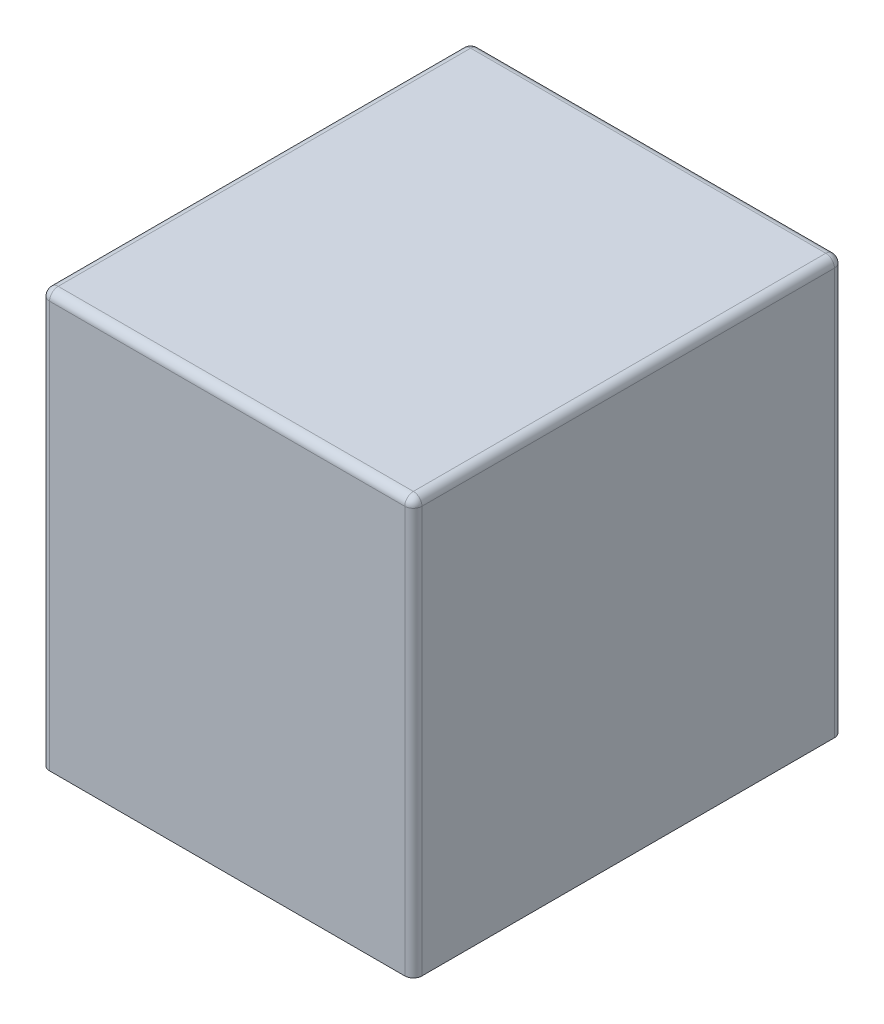
SolidWorks part; units mm, degrees
ref_plane "前视基准面" through (0, 0, 0) normal (0, 0, 1) x (1, 0, 0)
ref_plane "上视基准面" through (0, 0, 0) normal (0, 1, 0) x (1, 0, 0)
ref_plane "右视基准面" through (0, 0, 0) normal (1, 0, 0) x (0, 0, -1)
sketch "Sketch1" plane through (0, 0, 0) normal (0, 1, 0) x (1, 0, 0)
  line L0 (-65, 75) -> (65, 75)
  line L1 (-60, 70) -> (60, 70)
  line L2 (-60, 70) -> (-60, -70)
  line L3 (-60, -70) -> (60, -70)
  line L4 (60, 70) -> (60, -70)
  line L5 (-60, 70) -> (60, -70) construction
  line L6 (-60, -70) -> (60, 70) construction
  line L7 (65, 75) -> (65, -75)
  line L8 (-65, -75) -> (65, -75)
  line L9 (-65, 75) -> (-65, -75)
  point P0 (0, 0)
  dimension "D1" = 120
  dimension "D2" = 140
  dimension "D3" = 5
extrude "Boss-Extrude1" add sketch "Sketch1" along normal blind 140
sketch "Sketch2" plane through (0, 140, 0) normal (0, 1, 0) x (1, 0, 0)
  line L4 (-65, 75) -> (-65, -75)
  line L5 (-65, -75) -> (65, -75)
  line L6 (65, -75) -> (65, 75)
  line L7 (65, 75) -> (-65, 75)
  line L8 (-65, 75) -> (-65, -75)
  line L9 (-65, -75) -> (65, -75)
  line L10 (65, -75) -> (65, 75)
  line L11 (65, 75) -> (-65, 75)
  dimension "D1" = 0
extrude "Boss-Extrude2" add sketch "Sketch2" along normal blind 5
sketch "Sketch3" plane through (0, 0, 0) normal (0, -1, 0) x (1, 0, 0)
  line L0 (60, -70) -> (-60, -70) construction
  line L1 (60, 70) -> (60, -70) construction
  line L2 (-60, 70) -> (60, 70) construction
  line L3 (-60, -70) -> (-60, 70) construction
  line L4 (-65, 75) -> (-65, -75)
  line L5 (-65, -75) -> (65, -75)
  line L6 (65, -75) -> (65, 75)
  line L7 (65, 75) -> (-65, 75)
  line L8 (-65, 75) -> (-65, -75)
  line L9 (-65, -75) -> (65, -75)
  line L10 (65, -75) -> (65, 75)
  line L11 (65, 75) -> (-65, 75)
  line L12 (60, -70) -> (-60, -70)
  line L13 (60, 70) -> (60, -70)
  line L14 (-60, 70) -> (60, 70)
  line L15 (-60, -70) -> (-60, 70)
  line L16 (-62.5, 72.5) -> (62.5, 72.5)
  line L17 (62.5, 72.5) -> (62.5, -72.5)
  line L18 (62.5, -72.5) -> (-62.5, -72.5)
  line L19 (-62.5, -72.5) -> (-62.5, 72.5)
  circle A1 centre (0, 72.5) radius 1.45
  circle A2 centre (-62.5, 72.5) radius 1.45
  circle A3 centre (-62.5, -72.5) radius 1.45
  circle A4 centre (62.5, -72.5) radius 1.45
  circle A5 centre (62.5, 72.5) radius 1.45
  circle A6 centre (62.5, 0) radius 1.45
  circle A7 centre (-62.5, 0) radius 1.45
  circle A8 centre (0, -72.5) radius 1.45
  dimension "D2" = 2.5
  dimension "D1" = 0
extrude "Cut-Extrude1" cut sketch "Sketch3" against normal blind 12 contours L18 A8 | L18 A8 | L18 A4 L17 | L17 A4 L18 | L17 A6 | L17 A6 | L16 A5 L17 | L17 A5 L16 | L16 A1 | L16 A1 | L19 A2 L16 | L16 A2 L19 | L19 A7 | L19 A7 | L19 A3 L18 | L18 A3 L19
fillet "Fillet1" radius 3 8 edges at (65, 145, 0) (0, 145, 75) (-65, 145, 0) (0, 145, -75) (-65, 72.5, -75) (-65, 72.5, 75) (65, 72.5, 75) (65, 72.5, -75)
